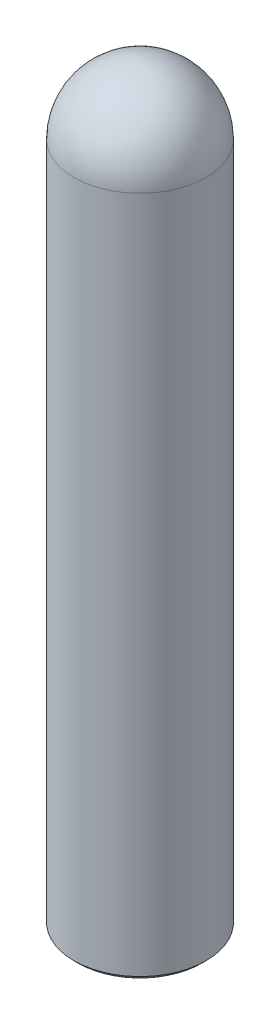
SolidWorks part; units mm, degrees
material "Custom Plastic"
ref_plane "Front Plane" through (0, 0, 0) normal (0, 0, 1) x (1, 0, 0)
ref_plane "Top Plane" through (0, 0, 0) normal (0, 1, 0) x (1, 0, 0)
ref_plane "Right Plane" through (0, 0, 0) normal (1, 0, 0) x (0, 0, -1)
sketch "Sketch1" plane through (0, 0, 0) normal (0, 1, 0) x (1, 0, 0)
  circle A0 centre (0, 0) radius 15
  dimension "D1" = 30
extrude "Boss-Extrude1" add sketch "Sketch1" along normal blind 170
fillet "Fillet1" radius 15 1 edges at (0, 170, 15)
sketch "Sketch2" plane through (0, 0, 0) normal (0, -1, 0) x (1, 0, 0)
  circle A0 centre (0, 0) radius 3.25
  dimension "D1" = 6.5
extrude "Cut-Extrude1" cut sketch "Sketch2" against normal blind 9.6
chamfer "Chamfer1" distance 0.4 angle 45 1 edges at (0, 0, -3.25)
chamfer "Chamfer2" distance 1 angle 45 1 edges at (0, 0, 15)
